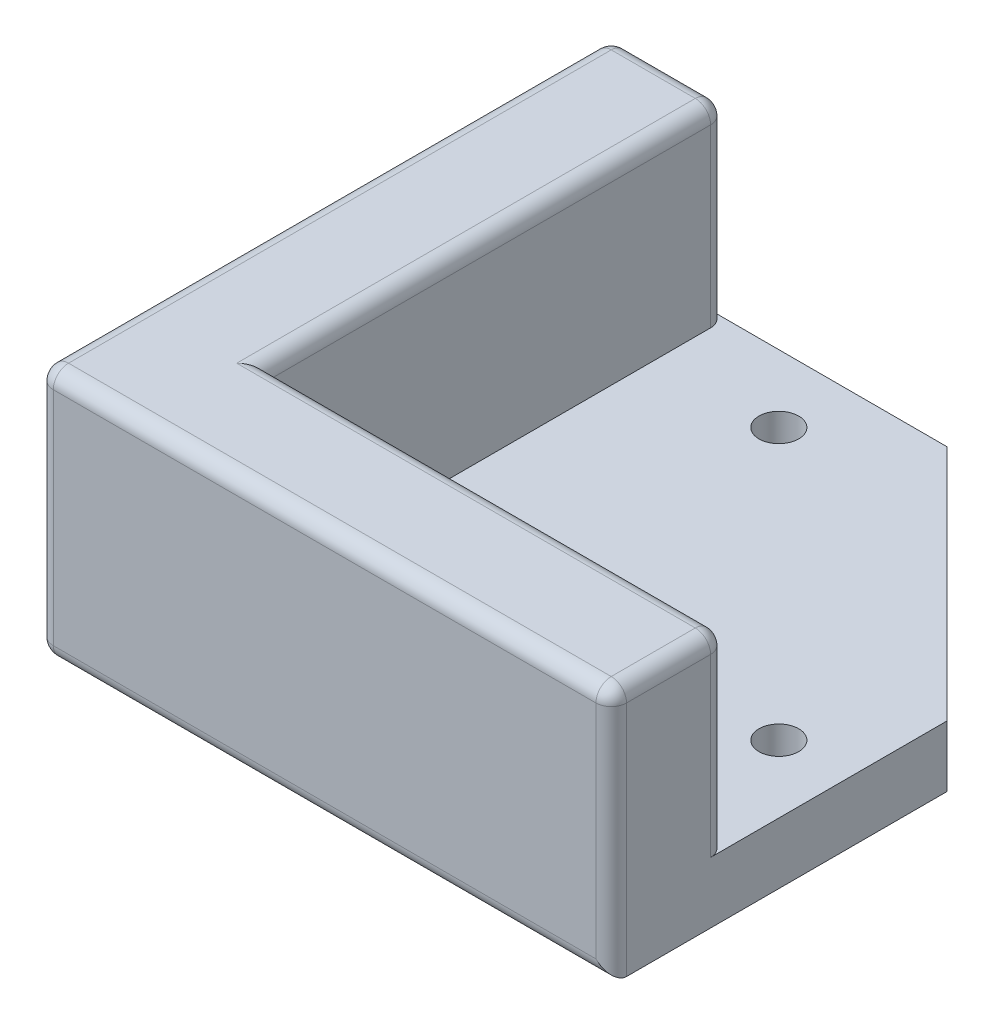
SolidWorks part; units mm, degrees
ref_plane "Front Plane" through (0, 0, 0) normal (0, 0, 1) x (1, 0, 0)
ref_plane "Top Plane" through (0, 0, 0) normal (0, 1, 0) x (1, 0, 0)
ref_plane "Right Plane" through (0, 0, 0) normal (1, 0, 0) x (0, 0, -1)
sketch "Sketch1" plane through (0, 0, 0) normal (0, 1, 0) x (1, 0, 0)
  line L0 (0, 0) -> (38.1, 0)
  line L1 (38.1, 0) -> (38.1, 2.3813)
  line L2 (38.1, 2.3813) -> (2.3813, 2.3812)
  line L3 (2.3813, 2.3812) -> (2.3812, 38.1)
  line L4 (2.3812, 38.1) -> (0, 38.1)
  line L5 (0, 38.1) -> (0, 0)
  dimension "D1" = 38.1
  dimension "D2" = 38.1
  dimension "D3" = 2.3813
  dimension "D4" = 2.3813
extrude "Boss-Extrude1" add sketch "Sketch1" along normal blind 2.54
sketch "Sketch2" plane through (0, 2.54, 0) normal (0, 1, 0) x (1, 0, 0)
  line L0 (2.3813, 2.3812) -> (2.3812, 38.1) construction
  line L1 (0, 38.1) -> (-9.525, 38.1)
  line L2 (0, 38.1) -> (0, 0)
  line L3 (0, 0) -> (-9.525, 0)
  line L4 (-9.525, 38.1) -> (-9.525, 0)
  line L5 (38.1, 0) -> (-9.525, 0)
  line L6 (38.1, 0) -> (38.1, -9.525)
  line L7 (38.1, -9.525) -> (-9.525, -9.525)
  line L8 (-9.525, 0) -> (-9.525, -9.525)
  line L9 (38.1, 2.3813) -> (2.3813, 2.3812) construction
  line M11 (0, 38.1) -> (0, 0)
  line M12 (0, 0) -> (38.1, 0)
  dimension "D1" = 11.9062
  dimension "D2" = 11.9062
extrude "Boss-Extrude2" add sketch "Sketch2" against normal blind 15.875 contours L1 L4 L3 M11 | L3 L8 L7 L6 M12
sketch "Sketch3" plane through (0, -13.335, 0) normal (0, -1, 0) x (-1, 0, 0)
  line L0 (-38.1, 0) -> (-38.1, -9.525) construction
  line L1 (9.525, -9.525) -> (-38.1, -9.525)
  line L2 (9.525, -9.525) -> (9.525, 38.1)
  line L3 (9.525, 38.1) -> (-18.3731, 38.1)
  line L4 (-38.1, -9.525) -> (-38.1, 18.3731)
  line L5 (0, 38.1) -> (9.525, 38.1) construction
  line L7 (-38.1, 18.3731) -> (-18.3731, 38.1)
  dimension "D1" = 45
extrude "Boss-Extrude3" add sketch "Sketch3" along normal blind 5.08
hole_wizard "M3 Clearance Hole1" positions "Sketch5" profile "Sketch6" hole size "M3" standard "ANSI Metric"
sketch "Sketch5" plane through (0, -18.415, 0) normal (0, -1, 0) x (-1, 0, 0)
  point P0 (-10, 32.5)
  point P2 (-32.5, 10)
  dimension "D1" = 32.5
  dimension "D2" = 32.5
  dimension "D3" = 10
  dimension "D4" = 10
sketch "Sketch6" plane through (10, -18.415, -32.5) normal (1, 0, 0) x (0, 0, -1)
  line L0 (0, 0) -> (0, 13.6914)
  line L1 (0, 13.6914) -> (1.65, 12.7)
  line L2 (1.65, 12.7) -> (1.65, 0)
  line L5 (1.65, 0) -> (0, 0)
  line L10 (0, 13.6914) -> (-1.65, 12.7) construction
  line L11 (0, -6.35) -> (0, 107.95) construction
  dimension "Hole Dia." = 3.3
  dimension "Hole Depth" = 12.7
  dimension "Drill Angle" = 118
sketch "Sketch7" plane through (0, 2.54, 0) normal (0, 1, 0) x (1, 0, 0)
  line L0 (2.3812, 0) -> (38.1, 0)
  line L1 (2.3812, 38.1) -> (0, 38.1)
  line L2 (2.3812, 38.1) -> (2.3812, 0)
  line L3 (2.3812, 0) -> (0, 0)
  line L4 (0, 38.1) -> (0, 0)
  line L9 (38.1, 0) -> (38.1, 2.3813)
  line L10 (38.1, 2.3813) -> (2.3813, 2.3812)
  line M1 (2.3812, 38.1) -> (-9.525, 38.1)
  line M4 (38.1, -9.525) -> (38.1, 2.3813)
  line M5 (38.1, 2.3813) -> (2.3813, 2.3812)
  line M6 (2.3813, 2.3812) -> (2.3812, 38.1)
extrude "Cut-Extrude1" cut sketch "Sketch7" against normal blind 2.54 contours L2 L0 M5 M4 | L4 L3 L2 M1 M6
fillet "Fillet1" radius 1.27 13 edges at (38.1, 2.54, 4.7625) (0, -5.3975, -38.1) (-9.525, -7.9375, -38.1) (38.1, -5.3975, 0) (14.2875, 2.54, 9.525) (38.1, -7.9375, 9.525) (-9.525, -7.9375, 9.525) (-9.525, 2.54, -14.2875) (-9.525, -18.415, -14.2875) (14.2875, -18.415, 9.525) (-4.7625, 2.54, -38.1) (0, 2.54, -19.05) (19.05, 2.54, 0)
